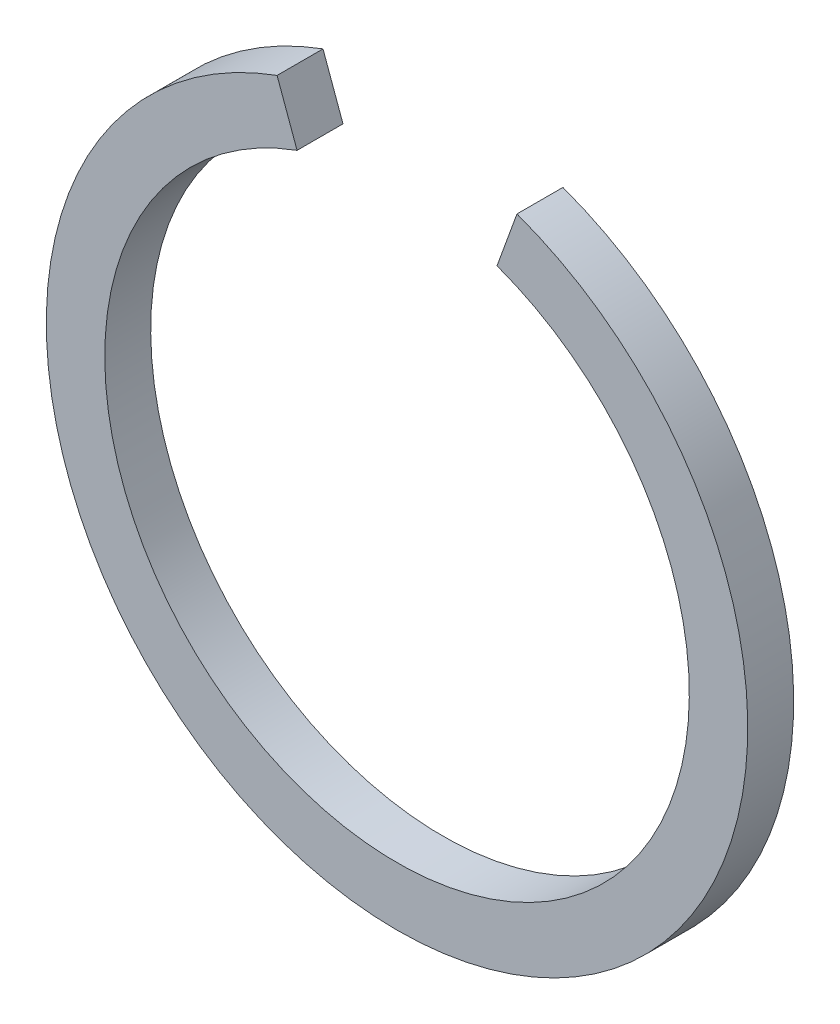
SolidWorks part; units mm, degrees
ref_plane "前视基准面" through (0, 0, 0) normal (0, 0, 1) x (1, 0, 0)
ref_plane "上视基准面" through (0, 0, 0) normal (0, 1, 0) x (1, 0, 0)
ref_plane "右视基准面" through (0, 0, 0) normal (1, 0, 0) x (0, 0, -1)
sketch "草图1" plane through (0, 0, 0) normal (0, 0, 1) x (1, 0, 0)
  circle A0 centre (0, 0) radius 8.4
  circle A1 centre (0, 0) radius 7
  dimension "D1" = 16.8
  dimension "D2" = 1.4
extrude "凸台-拉伸1" add sketch "草图1" along normal blind 1.1
sketch "草图2" plane through (0, 0, 1.1) normal (0, 0, 1) x (1, 0, 0)
  line L0 (0, 7) -> (0, 9.9632) construction
  line L1 (-2.3941, 6.5778) -> (-2.873, 7.8934)
  line L2 (2.3941, 6.5778) -> (2.873, 7.8934)
  line L3 (-2.873, 7.8934) -> (-3.5357, 9.7143) construction
  line L4 (0, 0) -> (-2.3941, 6.5778) construction
  line L5 (0, 0) -> (0, 7) construction
  line L6 (0, 0) -> (2.3941, 6.5778) construction
  line L7 (2.873, 7.8934) -> (3.5357, 9.7143) construction
  circle A0 centre (0, 0) radius 7 construction
  circle A1 centre (0, 0) radius 8.4 construction
  arc A2 (2.3941, 6.5778) -> (-2.3941, 6.5778) centre (0, 0) ccw
  arc A3 (2.873, 7.8934) -> (-2.873, 7.8934) centre (0, 0) ccw
  arc A4 (-2.873, 7.8934) -> (2.873, 7.8934) centre (0, 0) ccw construction
  arc A5 (-2.3941, 6.5778) -> (2.3941, 6.5778) centre (0, 0) ccw construction
  dimension "D1" = 40
extrude "切除-拉伸1" cut sketch "草图2" against normal blind 10
